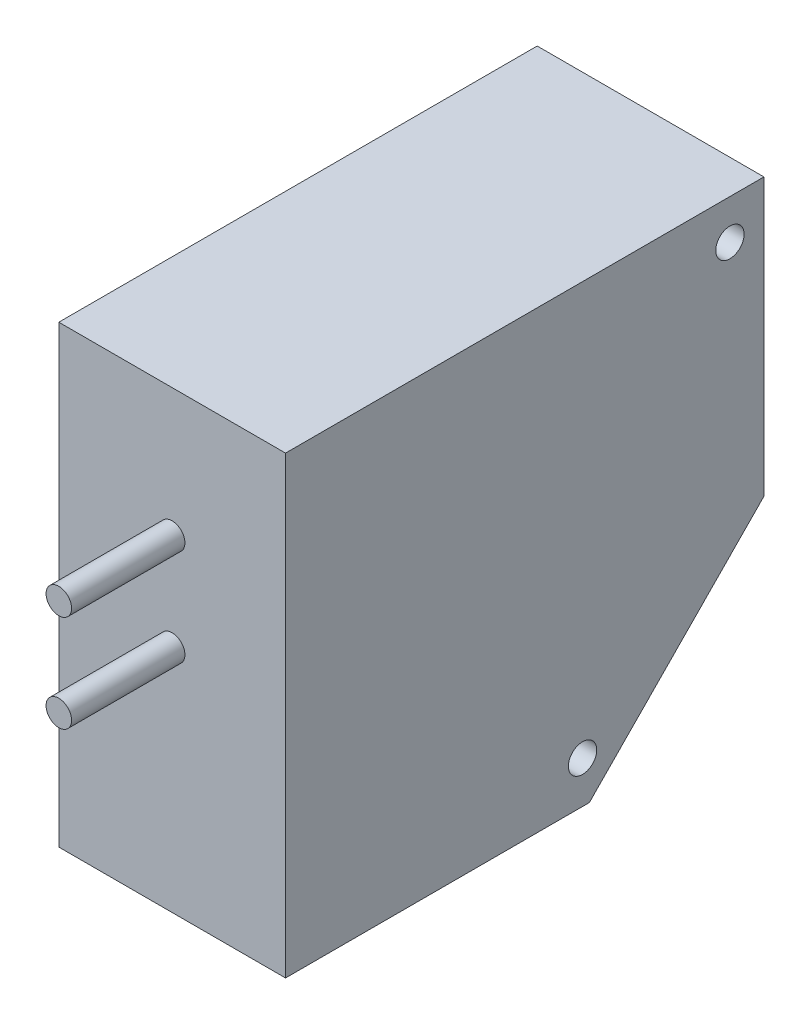
SolidWorks part; units mm, degrees
ref_plane "Front Plane" through (0, 0, 0) normal (0, 0, 1) x (1, 0, 0)
ref_plane "Top Plane" through (0, 0, 0) normal (0, 1, 0) x (1, 0, 0)
ref_plane "Right Plane" through (0, 0, 0) normal (1, 0, 0) x (0, 0, -1)
sketch "Sketch1" plane through (0, 0, 0) normal (1, 0, 0) x (0, 0, -1)
  line L0 (5.7, -20.05) -> (21.1, -4.35)
  line L1 (-21.1, 20.05) -> (21.1, 20.05)
  line L2 (-21.1, 20.05) -> (-21.1, -20.05)
  line L3 (-21.1, -20.05) -> (5.7, -20.05)
  line L4 (21.1, 20.05) -> (21.1, -4.35)
  line L5 (0, 0) -> (-21.1, 20.05) construction
  line L6 (-21.1, -20.05) -> (21.1, 20.05) construction
  line L7 (0, 0) -> (21.1, -20.05) construction
  line L8 (21.1, -20.05) -> (21.1, -4.35) construction
  line L9 (21.1, -20.05) -> (5.7, -20.05) construction
  point P0 (0, 0)
  dimension "D1" = 42.2
  dimension "D2" = 40.1
  dimension "D3" = 24.4
  dimension "D4" = 26.8
extrude "Boss-Extrude1" add sketch "Sketch1" along normal blind 20
hole_wizard "Ø2.5 (2.5) Diameter Hole1" positions "Sketch3" profile "Sketch2" hole size "Ø2.5" standard "ISO" end condition up to next
sketch "Sketch3" plane through (20, 0, 0) normal (1, 0, 0) x (0, 0, -1)
  line L0 (21.1, 20.05) -> (-21.1, 20.05) construction
  line L1 (21.1, -4.35) -> (21.1, 20.05) construction
  point P0 (18.1, 16.55)
  dimension "D1" = 3.5
  dimension "D2" = 3
sketch "Sketch2" plane through (20, 16.55, -18.1) normal (0, 1, 0) x (0, 0, -1)
  line L0 (0, 0) -> (0, 20)
  line L1 (0, 20) -> (1.25, 20)
  line L2 (1.25, 20) -> (1.25, 0)
  line L5 (1.25, 0) -> (0, 0)
  line L11 (0, -6.35) -> (0, 107.95) construction
  dimension "Thru Hole Dia." = 2.5
  dimension "Thru Hole Depth" = 20
hole_wizard "Ø2.5 (2.5) Diameter Hole2" positions "Sketch5" profile "Sketch4" hole size "Ø2.5" standard "ISO" end condition up to next
sketch "Sketch5" plane through (20, 0, 0) normal (1, 0, 0) x (0, 0, -1)
  line L0 (21.1, 20.05) -> (-21.1, 20.05) construction
  line L1 (21.1, -4.35) -> (21.1, 20.05) construction
  point P0 (5.1, -16.35)
  dimension "D1" = 36.4
  dimension "D2" = 16
sketch "Sketch4" plane through (20, -16.35, -5.1) normal (0, 1, 0) x (0, 0, -1)
  line L0 (0, 0) -> (0, 20)
  line L1 (0, 20) -> (1.25, 20)
  line L2 (1.25, 20) -> (1.25, 0)
  line L5 (1.25, 0) -> (0, 0)
  line L11 (0, -6.35) -> (0, 107.95) construction
  dimension "Thru Hole Dia." = 2.5
  dimension "Thru Hole Depth" = 20
sketch "Sketch6" plane through (0, 0, 21.1) normal (0, 0, 1) x (1, 0, 0)
  line L0 (10, 20.05) -> (10, -20.05) construction
  line L1 (20, 20.05) -> (0, 20.05) construction
  line L2 (20, -20.05) -> (0, -20.05) construction
  circle A0 centre (10, 8.75) radius 1.125
  circle A1 centre (10, 0.2) radius 1.125
  dimension "D1" = 2.25
  dimension "D2" = 11.3
  dimension "D3" = 19.85
extrude "Boss-Extrude2" add sketch "Sketch6" along normal blind 10
